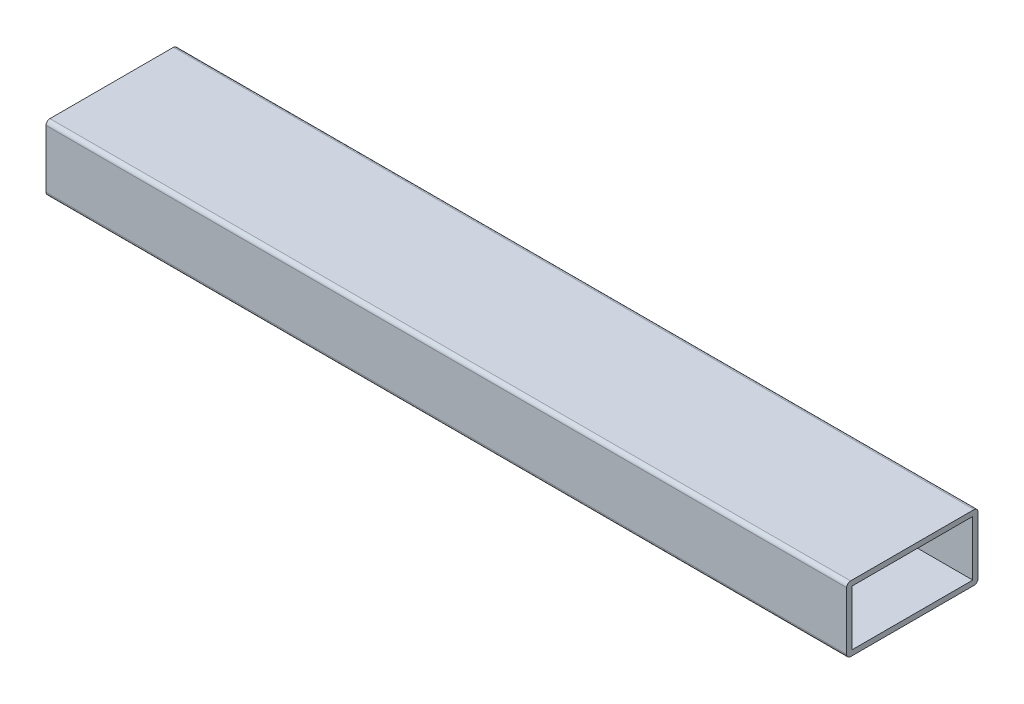
SolidWorks part; units mm, degrees
ref_plane "Front Plane" through (0, 0, 0) normal (0, 0, 1) x (1, 0, 0)
ref_plane "Top Plane" through (0, 0, 0) normal (0, 1, 0) x (1, 0, 0)
ref_plane "Right Plane" through (0, 0, 0) normal (1, 0, 0) x (0, 0, -1)
sketch "Sketch1" plane through (0, 0, 0) normal (1, 0, 0) x (0, 0, -1)
  line L1 (-23.5, 12.5) -> (23.5, 12.5)
  line L2 (-25, 11) -> (-25, -11)
  line L3 (-23.5, -12.5) -> (23.5, -12.5)
  line L4 (25, 11) -> (25, -11)
  line L5 (-25, 12.5) -> (25, -12.5) construction
  line L6 (-25, -12.5) -> (25, 12.5) construction
  arc A0 (-23.5, -12.5) -> (-25, -11) centre (-23.5, -11) cw
  arc A1 (23.5, -12.5) -> (25, -11) centre (23.5, -11) ccw
  arc A2 (25, 11) -> (23.5, 12.5) centre (23.5, 11) ccw
  arc A3 (-25, 11) -> (-23.5, 12.5) centre (-23.5, 11) cw
  point P0 (0, 0)
  dimension "D3" = 1.5
  dimension "D1" = 50
  dimension "D2" = 25
extrude "Boss-Extrude1" add sketch "Sketch1" along normal mid plane 304.8
shell "Shell1" thickness 2
